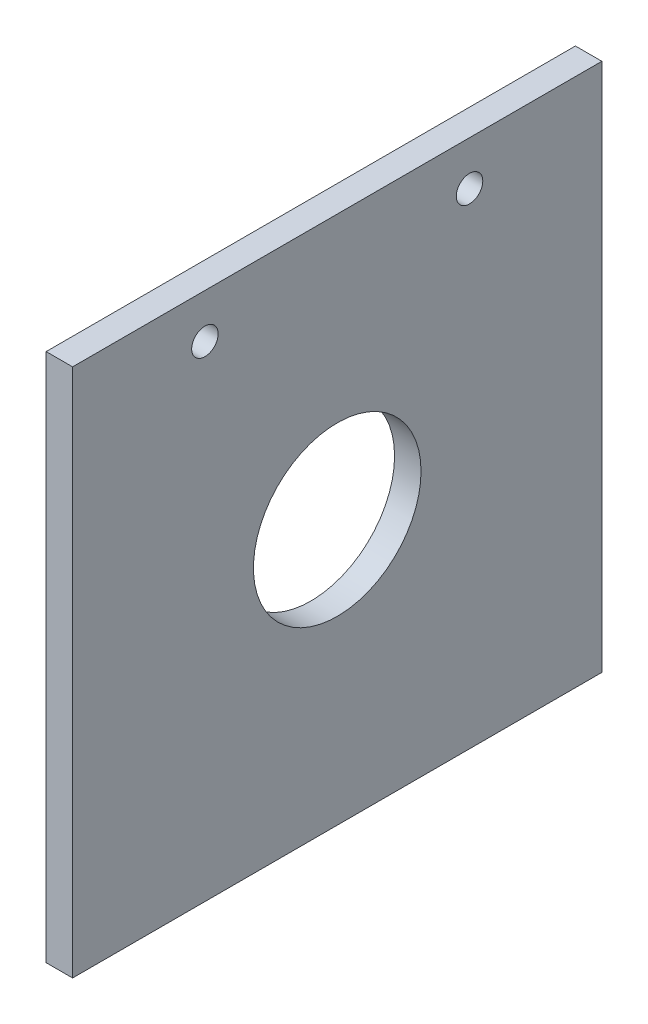
SolidWorks part; units mm, degrees
material "Perspex (TM) GS Acrylic Cast Sheet"
ref_plane "Ebene vorne" through (0, 0, 0) normal (0, 0, 1) x (1, 0, 0)
ref_plane "Ebene oben" through (0, 0, 0) normal (0, 1, 0) x (1, 0, 0)
ref_plane "Ebene rechts" through (0, 0, 0) normal (1, 0, 0) x (0, 0, -1)
sketch "Skizze1" plane through (0, 0, 0) normal (1, 0, 0) x (0, 0, -1)
  line L1 (-30, 30) -> (30, 30)
  line L2 (-30, 30) -> (-30, -30)
  line L3 (-30, -30) -> (30, -30)
  line L4 (30, 30) -> (30, -30)
  line L5 (-30, 30) -> (30, -30) construction
  line L6 (-30, -30) -> (30, 30) construction
  point P0 (0, 0)
  dimension "D1" = 60
  dimension "D2" = 60
extrude "Aufsatz-Linear austragen1" add sketch "Skizze1" along normal blind 3
sketch "Skizze3" plane through (3, 0, 0) normal (1, 0, 0) x (0, 0, -1)
  line L0 (30, 30) -> (-30, 30) construction
  line L1 (0, 30) -> (30, 30) construction
  line L2 (0, 30) -> (0, 20) construction
  line L3 (0, 20) -> (30, 20) construction
  line L4 (30, 30) -> (30, 20) construction
  line L5 (0, 30) -> (30, 20) construction
  line L6 (0, 20) -> (30, 30) construction
  line L7 (30, -30) -> (30, 30) construction
  line L9 (0, 20) -> (-30, 20) construction
  line L10 (0, 20) -> (0, 30) construction
  line L11 (0, 30) -> (-30, 30) construction
  line L12 (-30, 20) -> (-30, 30) construction
  line L13 (0, 20) -> (-30, 30) construction
  line L14 (0, 30) -> (-30, 20) construction
  circle A0 centre (-15, 25) radius 1.5
  circle A1 centre (15, 25) radius 1.5
  circle A2 centre (0, 0) radius 9.5
  point P4 (15, 25)
  point P11 (-15, 25)
  dimension "D2" = 3
  dimension "D3" = 19
  dimension "D1" = 10
extrude "Schnitt-Linear austragen2" cut sketch "Skizze3" against normal through all
